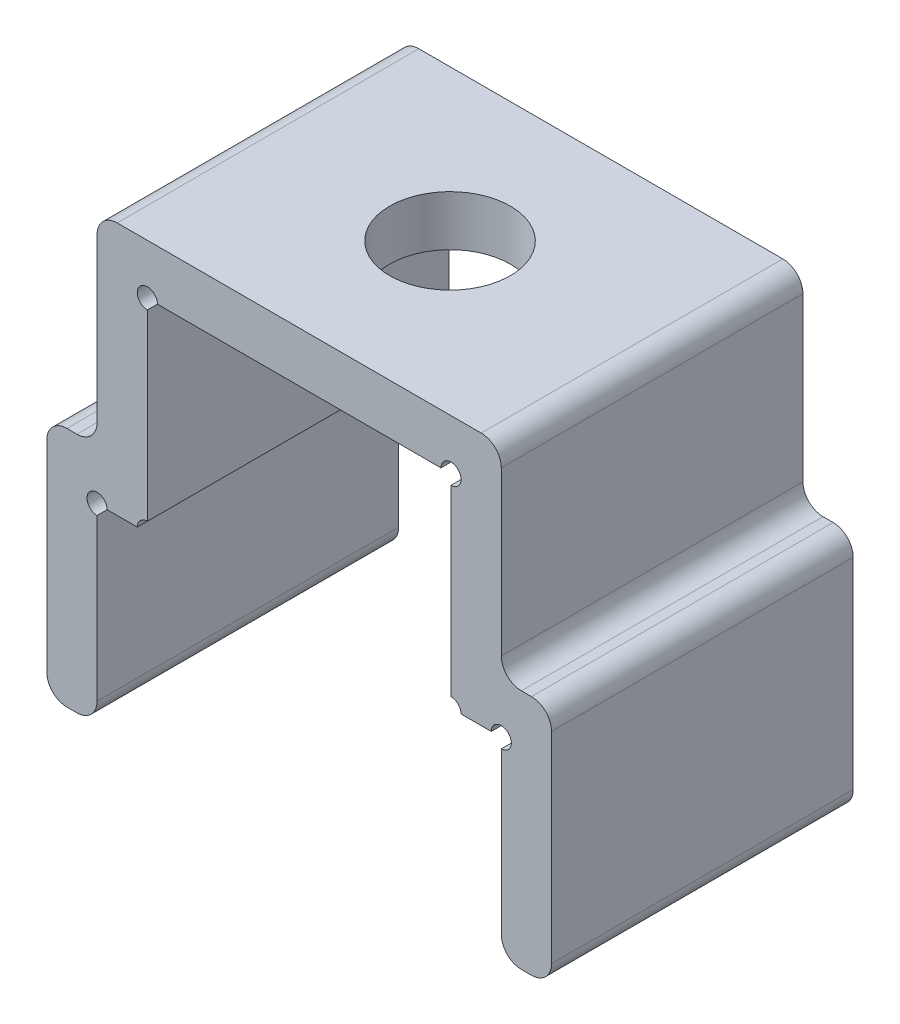
SolidWorks part; units mm, degrees
ref_plane "Alzado" through (0, 0, 0) normal (0, 0, 1) x (1, 0, 0)
ref_plane "Planta" through (0, 0, 0) normal (0, 1, 0) x (1, 0, 0)
ref_plane "Vista lateral" through (0, 0, 0) normal (1, 0, 0) x (0, 0, -1)
sketch "Croquis1" plane through (0, 0, 0) normal (0, 0, 1) x (1, 0, 0)
  line L0 (-9.55, -5.05) -> (-8.05, -5.05)
  line L1 (7.05, 5.05) -> (-7.05, 5.05)
  line L2 (7.55, 4.55) -> (7.55, -4.55)
  line L4 (-7.55, 4.55) -> (-7.55, -4.55)
  line L5 (7.55, 5.05) -> (-7.1344, -4.772) construction
  line L6 (10.05, -5.05) -> (10.05, -25.05) construction
  line L7 (10.05, -5.55) -> (10.05, -13.55)
  line L9 (-10.05, -13.55) -> (-10.05, -5.55)
  line L10 (8.05, -5.05) -> (9.55, -5.05)
  line L11 (-11.55, -2.55) -> (-11.05, -2.55)
  line L12 (-10.05, 6.55) -> (-10.05, -1.55)
  line L13 (9.05, 7.55) -> (-9.05, 7.55)
  line L14 (10.05, 6.55) -> (10.05, -1.55)
  line L15 (11.05, -2.55) -> (11.55, -2.55)
  line L16 (12.55, -3.55) -> (12.55, -13.55)
  line L18 (-12.55, -13.55) -> (-12.55, -3.55)
  line L19 (-11.05, -14.55) -> (-11.55, -14.55)
  line L20 (11.05, -14.55) -> (11.55, -14.55)
  line L21 (-12.55, -27.55) -> (-12.55, -2.55) construction
  line L22 (12.55, -2.55) -> (12.55, -27.55) construction
  line L23 (12.55, -27.55) -> (-12.55, -27.55) construction
  line L24 (10.05, -25.05) -> (-10.05, -25.05) construction
  line L25 (-10.05, -25.05) -> (-10.05, -5.05) construction
  line L26 (-10.05, -5.05) -> (-7.55, -5.05) construction
  line L27 (-7.55, 5.05) -> (-7.55, -5.05) construction
  line L28 (7.55, 5.05) -> (-7.55, 5.05) construction
  line L29 (7.55, 5.05) -> (7.55, -5.05) construction
  line L30 (0, 0) -> (-7.1344, 4.772) construction
  line L31 (7.55, -5.05) -> (10.05, -5.05) construction
  line L32 (10.05, -2.55) -> (12.55, -2.55) construction
  line L33 (10.05, 7.55) -> (10.05, -2.55) construction
  line L34 (10.05, 7.55) -> (-10.05, 7.55) construction
  line L35 (-12.55, -2.55) -> (-10.05, -2.55) construction
  line L36 (-10.05, 7.55) -> (-10.05, -2.55) construction
  arc A0 (-7.05, 5.05) -> (-7.55, 4.55) centre (-7.55, 5.05) ccw
  arc A1 (7.55, 4.55) -> (7.05, 5.05) centre (7.55, 5.05) ccw
  arc A2 (8.05, -5.05) -> (7.55, -4.55) centre (7.55, -5.05) ccw
  arc A3 (10.05, -5.55) -> (9.55, -5.05) centre (10.05, -5.05) ccw
  arc A4 (-9.55, -5.05) -> (-10.05, -5.55) centre (-10.05, -5.05) ccw
  arc A5 (-7.55, -4.55) -> (-8.05, -5.05) centre (-7.55, -5.05) ccw
  arc A6 (-10.05, -13.55) -> (-11.05, -14.55) centre (-11.05, -13.55) cw
  arc A7 (11.05, -14.55) -> (10.05, -13.55) centre (11.05, -13.55) cw
  arc A8 (11.55, -14.55) -> (12.55, -13.55) centre (11.55, -13.55) ccw
  arc A9 (-12.55, -13.55) -> (-11.55, -14.55) centre (-11.55, -13.55) ccw
  arc A10 (11.55, -2.55) -> (12.55, -3.55) centre (11.55, -3.55) cw
  arc A11 (10.05, -1.55) -> (11.05, -2.55) centre (11.05, -1.55) ccw
  arc A12 (10.05, 6.55) -> (9.05, 7.55) centre (9.05, 6.55) ccw
  arc A13 (-11.05, -2.55) -> (-10.05, -1.55) centre (-11.05, -1.55) ccw
  arc A14 (-11.55, -2.55) -> (-12.55, -3.55) centre (-11.55, -3.55) ccw
  arc A15 (-10.05, 6.55) -> (-9.05, 7.55) centre (-9.05, 6.55) cw
  point P0 (0, 0)
  dimension "D8" = 1
  dimension "D9" = 1
  dimension "D10" = 1
  dimension "D11" = 1
  dimension "D12" = 1
  dimension "D13" = 1
  dimension "D6" = 1
  dimension "D1" = 15.1
  dimension "D2" = 10.1
  dimension "D3" = 20.1
  dimension "D4" = 10
  dimension "D5" = 10.05
  dimension "D7" = 2.5
  dimension "D14" = 10
extrude "Saliente-Extruir1" add sketch "Croquis1" along normal blind 15
sketch "Croquis2" plane through (0, 7.55, 0) normal (0, 1, 0) x (1, 0, 0)
  circle A0 centre (0, -7.5) radius 3
  point P2 (0, -7.5)
  dimension "D1" = 6
extrude "Cortar-Extruir1" cut sketch "Croquis2" against normal blind 20
